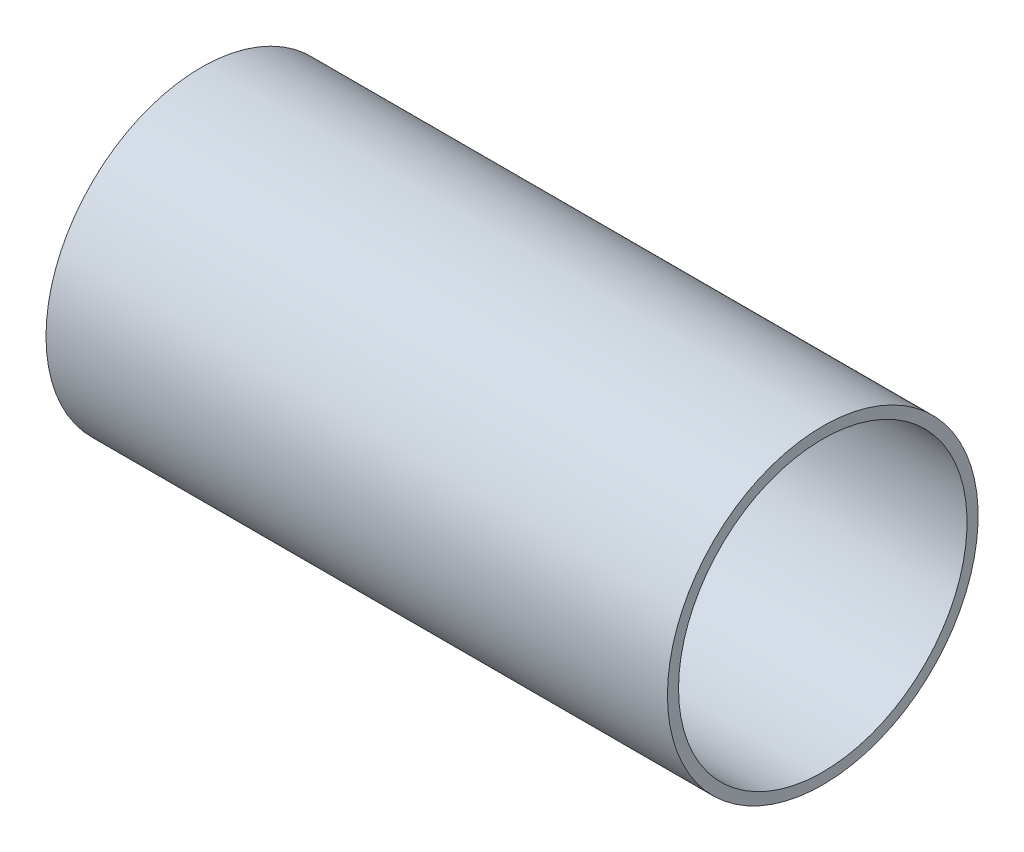
SolidWorks part; units mm, degrees
ref_plane "Plan de face" through (0, 0, 0) normal (0, 0, 1) x (1, 0, 0)
ref_plane "Plan de dessus" through (0, 0, 0) normal (0, 1, 0) x (1, 0, 0)
ref_plane "Plan de droite" through (0, 0, 0) normal (1, 0, 0) x (0, 0, -1)
sketch "Esquisse1" plane through (0, 0, 0) normal (0, 0, 1) x (1, 0, 0)
  line L0 (-77.9361, 0) -> (85.5718, 0) construction
  line L1 (-28.4362, 6.5) -> (-0.4362, 6.5)
  line L2 (-0.4362, 6.5) -> (-0.4362, 7)
  line L3 (-0.4362, 7) -> (-28.4362, 7)
  line L4 (-28.4362, 7) -> (-28.4362, 6.5)
  dimension "D1" = 28
  dimension "D2" = 6.5
  dimension "D3" = 7
revolve "Révolution1" add sketch "Esquisse1" angle 360 about L0
